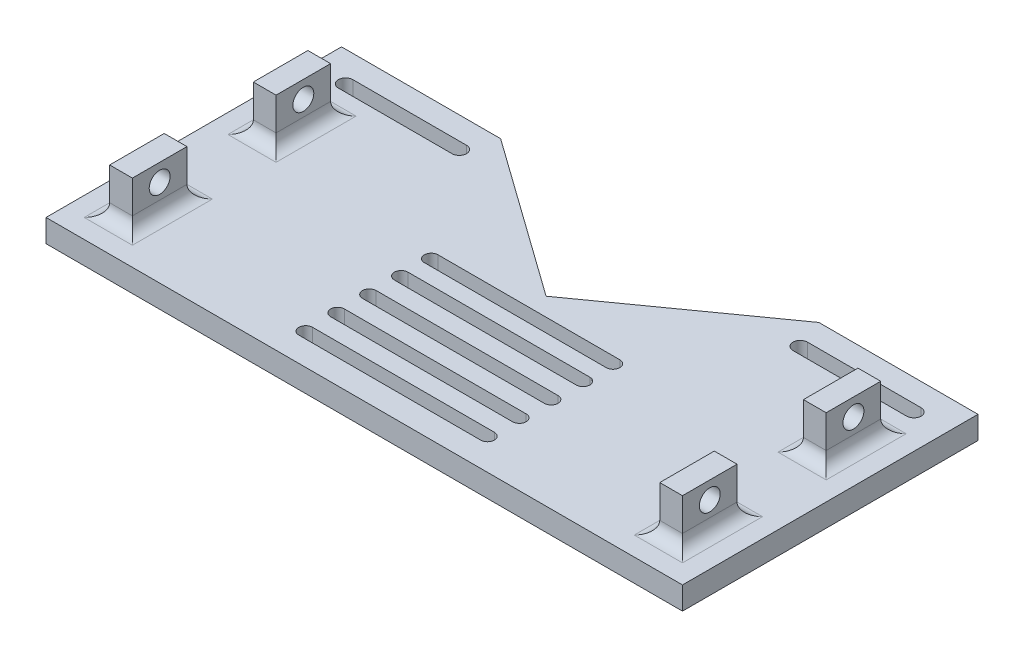
SolidWorks part; units mm, degrees
ref_plane "Plan de face" through (0, 0, 0) normal (0, 0, 1) x (1, 0, 0)
ref_plane "Plan de dessus" through (0, 0, 0) normal (0, 1, 0) x (1, 0, 0)
ref_plane "Plan de droite" through (0, 0, 0) normal (1, 0, 0) x (0, 0, -1)
sketch "Esquisse1" plane through (0, 0, 0) normal (0, 1, 0) x (1, 0, 0)
  line L0 (-70, 20.3915) -> (-70, 45.3915)
  line L2 (-70, 20.3915) -> (-70, -19.6085)
  line L3 (-70, -19.6085) -> (70, -19.6085)
  line L4 (70, 20.3915) -> (70, -19.6085)
  line L5 (-19.7686, 1.283) -> (20.2314, 1.283) construction
  line L6 (-19.7686, 2.783) -> (20.2314, 2.783)
  line L7 (-70, 45.3915) -> (-35, 45.3915)
  line L8 (-35, 45.3915) -> (0, 20.3915)
  line L9 (0, 20.3915) -> (35, 45.3915)
  line L10 (35, 45.3915) -> (70, 45.3915)
  line L11 (70, 45.3915) -> (70, 20.3915)
  line L12 (-70, 45.3915) -> (-70, 20.3915)
  line L13 (-19.7686, -0.217) -> (20.2314, -0.217)
  line L14 (-19.7686, 8.283) -> (20.2314, 8.283) construction
  line L15 (-19.7686, 9.783) -> (20.2314, 9.783)
  line L16 (-19.7686, 6.783) -> (20.2314, 6.783)
  line L17 (-19.7686, 14.8915) -> (20.2314, 14.8915) construction
  line L18 (-19.7686, 16.3915) -> (20.2314, 16.3915)
  line L19 (-19.7686, 13.3915) -> (20.2314, 13.3915)
  line L20 (-19.7686, -5.717) -> (20.2314, -5.717) construction
  line L21 (-19.7686, -4.217) -> (20.2314, -4.217)
  line L22 (-19.7686, -7.217) -> (20.2314, -7.217)
  line L23 (-19.7686, -12.717) -> (20.2314, -12.717) construction
  line L24 (-19.7686, -11.217) -> (20.2314, -11.217)
  line L25 (-19.7686, -14.217) -> (20.2314, -14.217)
  line L26 (-62.5, 38.7929) -> (-37.5, 38.7929) construction
  line L29 (-62.5, 40.3915) -> (-37.5, 40.3915)
  line L32 (-62.5, 37.1942) -> (-37.5, 37.1942)
  line L35 (37.5, 38.7915) -> (62.5, 38.7915) construction
  line L38 (37.5, 40.3915) -> (62.5, 40.3915)
  line L41 (37.5, 37.1915) -> (62.5, 37.1915)
  arc A0 (-19.7686, 2.783) -> (-19.7686, -0.217) centre (-19.7686, 1.283) ccw
  arc A1 (20.2314, -0.217) -> (20.2314, 2.783) centre (20.2314, 1.283) ccw
  arc A2 (-19.7686, 9.783) -> (-19.7686, 6.783) centre (-19.7686, 8.283) ccw
  arc A3 (20.2314, 6.783) -> (20.2314, 9.783) centre (20.2314, 8.283) ccw
  arc A4 (-19.7686, 16.3915) -> (-19.7686, 13.3915) centre (-19.7686, 14.8915) ccw
  arc A5 (20.2314, 13.3915) -> (20.2314, 16.3915) centre (20.2314, 14.8915) ccw
  arc A6 (-19.7686, -4.217) -> (-19.7686, -7.217) centre (-19.7686, -5.717) ccw
  arc A7 (20.2314, -7.217) -> (20.2314, -4.217) centre (20.2314, -5.717) ccw
  arc A8 (-19.7686, -11.217) -> (-19.7686, -14.217) centre (-19.7686, -12.717) ccw
  arc A9 (20.2314, -14.217) -> (20.2314, -11.217) centre (20.2314, -12.717) ccw
  arc A20 (-62.5, 40.3915) -> (-62.5, 37.1942) centre (-62.5, 38.7929) ccw
  arc A21 (-37.5, 37.1942) -> (-37.5, 40.3915) centre (-37.5, 38.7929) ccw
  arc A22 (37.5, 40.3915) -> (37.5, 37.1915) centre (37.5, 38.7915) ccw
  arc A23 (62.5, 37.1915) -> (62.5, 40.3915) centre (62.5, 38.7915) ccw
  point P0 (0, 0)
  point P13 (0.2314, 1.283)
  point P20 (0.2314, 8.283)
  point P27 (0.2314, 14.8915)
  point P34 (0.2314, -5.717)
  point P41 (0.2314, -12.717)
  point P48 (-50, 38.7929)
  point P56 (50, 38.7915)
  dimension "D8" = 100
  dimension "D1" = 140
  dimension "D2" = 40
  dimension "D3" = 65
  dimension "D4" = 65
  dimension "D5" = 35
  dimension "D6" = 35
  dimension "D7" = 40
  dimension "D9" = 20
  dimension "D10" = 5
  dimension "D11" = 5
  dimension "D12" = 20.8027
  dimension "D13" = 20.8
  dimension "D14" = 49.7686
extrude "Boss.-Extru.1" add sketch "Esquisse1" along normal blind 5 contours L11 L10 L9 L8 L7 L0 L2 L3 L4 A23 L41 A22 L38 A21 L32 A20 L29 A9 L25 A8 L24 A7 L22 A6 L21 A5 L19 A4 L18 A3 L16 A2 L15 A1 L13 A0 L6
sketch "Esquisse2" plane through (0, 5, 0) normal (0, 1, 0) x (1, 0, 0)
sketch "Esquisse3" plane through (0, 5, 0) normal (0, 1, 0) x (1, 0, 0)
  line L0 (-70, -19.6085) -> (-70, 45.3915) construction
  line L1 (-63, 30.9922) -> (-58, 30.9922)
  line L2 (-63, 30.9922) -> (-63, 18.9922)
  line L3 (-63, 18.9922) -> (-58, 18.9922)
  line L4 (-58, 30.9922) -> (-58, 18.9922)
  line L5 (-63, -0.6085) -> (-58, -0.6085)
  line L6 (-63, -0.6085) -> (-63, -12.6085)
  line L7 (-63, -12.6085) -> (-58, -12.6085)
  line L8 (-58, -0.6085) -> (-58, -12.6085)
  line L9 (-70, -19.6085) -> (70, -19.6085) construction
  line L10 (0, -2.75) -> (0, 2.75) construction
  line L11 (63, -0.6085) -> (63, -12.6085)
  line L12 (63, -12.6085) -> (58, -12.6085)
  line L13 (58, -0.6085) -> (58, -12.6085)
  line L14 (63, -0.6085) -> (58, -0.6085)
  line L15 (63, 18.9922) -> (58, 18.9922)
  line L16 (58, 30.9922) -> (58, 18.9922)
  line L17 (63, 30.9922) -> (58, 30.9922)
  line L18 (63, 30.9922) -> (63, 18.9922)
  point P10 (-60.5, -12.6085)
  dimension "D1" = 7
  dimension "D2" = 5
  dimension "D3" = 12
  dimension "D4" = 7
  dimension "D5" = 7
  dimension "D6" = 12
extrude "Boss.-Extru.2" add sketch "Esquisse3" along normal blind 10
sketch "Esquisse4" plane through (-63, 0, 0) normal (-1, 0, 0) x (0, 0, 1)
  line L0 (-24.9922, 15) -> (-24.9922, 5) construction
  line L1 (-30.9922, 15) -> (-18.9922, 15) construction
  line L2 (-30.9922, 5) -> (-18.9922, 5) construction
  line L3 (0.6085, 5) -> (12.6085, 5) construction
  circle A0 centre (-24.9922, 11.2) radius 2.3
  circle A1 centre (6.6056, 11.2) radius 2.3
  dimension "D1" = 6.2
  dimension "D2" = 6.2
extrude "Enlèv. mat.-Extru.1" cut sketch "Esquisse4" against normal through all
fillet "Congé1" radius 2.8 16 edges at (60.5, 5, 0.6085) (60.5, 5, -30.9922) (58, 5, 6.6085) (58, 5, -24.9922) (60.5, 5, 12.6085) (60.5, 5, -18.9922) (63, 5, -24.9922) (63, 5, 6.6085) (-60.5, 5, 0.6085) (-58, 5, 6.6085) (-60.5, 5, 12.6085) (-63, 5, 6.6085) (-60.5, 5, -30.9922) (-58, 5, -24.9922) (-60.5, 5, -18.9922) (-63, 5, -24.9922)
ref_plane "Plan3" through (63, 7.8, -30.9922) normal (0, -1, 0) x (-1, 0, 0)
sketch "Esquisse10" plane through (-63, 0, 0) normal (-1, 0, 0) x (0, 0, 1)
  line L2 (-24.9922, 8.9) -> (-23.6908, 8.9) construction
  line L4 (-30.9922, 15) -> (-30.9922, 7.8) construction
  line L5 (12.6085, 15) -> (12.6085, 7.8) construction
  circle A1 centre (-24.9922, 11.2) radius 2.3 construction
